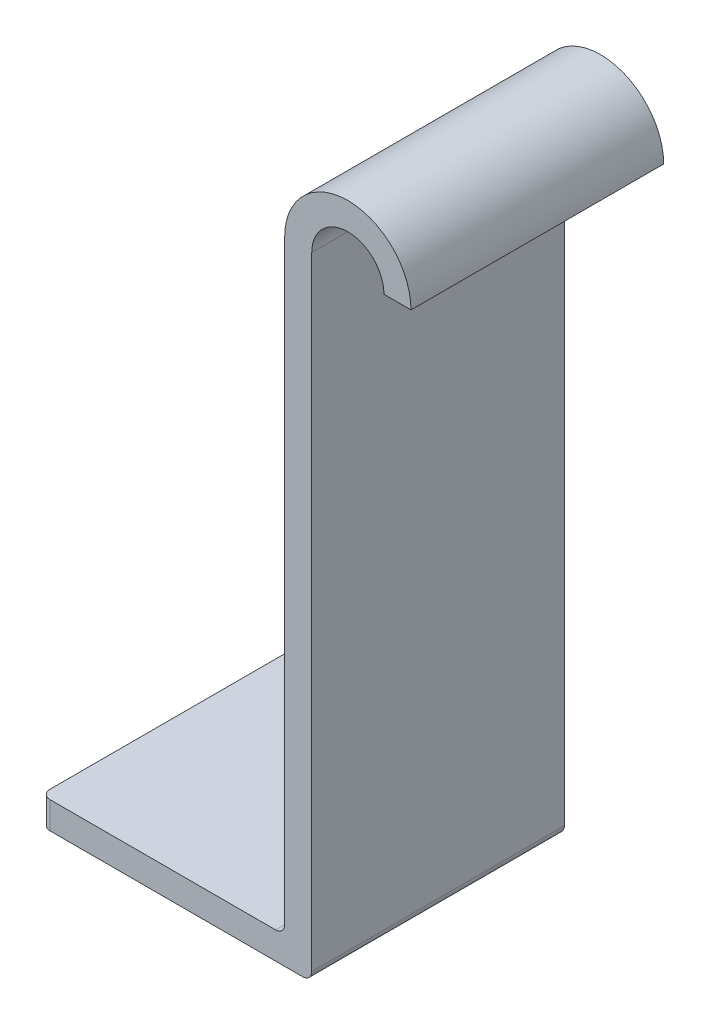
SolidWorks part; units mm, degrees
ref_plane "Спереди" through (0, 0, 0) normal (0, 0, 1) x (1, 0, 0)
ref_plane "Сверху" through (0, 0, 0) normal (0, 1, 0) x (1, 0, 0)
ref_plane "Справа" through (0, 0, 0) normal (1, 0, 0) x (0, 0, -1)
sketch "Sketch1" plane through (0, 0, 0) normal (0, 0, 1) x (1, 0, 0)
  line L0 (0, 0) -> (0, -70)
  line L1 (0, -70) -> (-30, -70)
  line L2 (-3, 0) -> (-3, -67)
  line L3 (-3, -67) -> (-30, -67)
  line L4 (8, 0) -> (11, 0)
  line L5 (-30, -70) -> (-30, -67)
  arc A0 (0, 0) -> (8, 0) centre (4, 0) cw
  arc A1 (-3, 0) -> (11, 0) centre (4, 0) cw
  dimension "D2" = 4
  dimension "D1" = 70
  dimension "D3" = 30
  dimension "D4" = 3
extrude "Boss-Extrude1" add sketch "Sketch1" along normal blind 28
fillet "Fillet1" radius 1 4 edges at (-30, -68.5, 0) (-30, -68.5, 28) (0, -70, 14) (-3, -67, 14)
